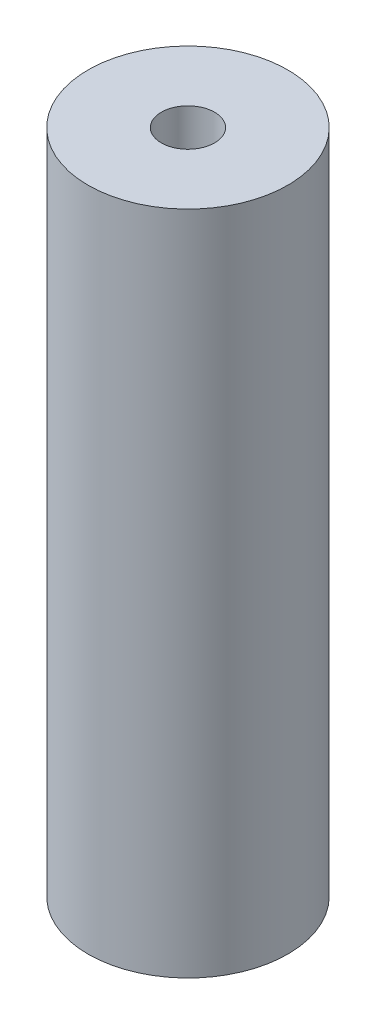
SolidWorks part; units mm, degrees
ref_plane "Front Plane" through (0, 0, 0) normal (0, 0, 1) x (1, 0, 0)
ref_plane "Top Plane" through (0, 0, 0) normal (0, 1, 0) x (1, 0, 0)
ref_plane "Right Plane" through (0, 0, 0) normal (1, 0, 0) x (0, 0, -1)
sketch "Sketch1" plane through (0, 0, 0) normal (0, 1, 0) x (1, 0, 0)
  circle A0 centre (0, 0) radius 4.5
  dimension "D1" = 9
extrude "Boss-Extrude1" add sketch "Sketch1" along normal blind 30
sketch "Sketch2" plane through (0, 30, 0) normal (0, 1, 0) x (1, 0, 0)
  circle A0 centre (0, 0) radius 3.05
  dimension "D1" = 6.1
extrude "Cut-Extrude1" cut sketch "Sketch2" against normal through all
sketch "Sketch3" plane through (0, 30, 0) normal (0, 1, 0) x (1, 0, 0)
  circle A0 centre (0, 0) radius 3.05
extrude "Boss-Extrude2" add sketch "Sketch3" against normal blind 10
sketch "Sketch4" plane through (0, 30, 0) normal (0, 1, 0) x (1, 0, 0)
  circle A0 centre (0, 0) radius 1.2
  dimension "D1" = 2.4
extrude "Cut-Extrude2" cut sketch "Sketch4" against normal blind 10
